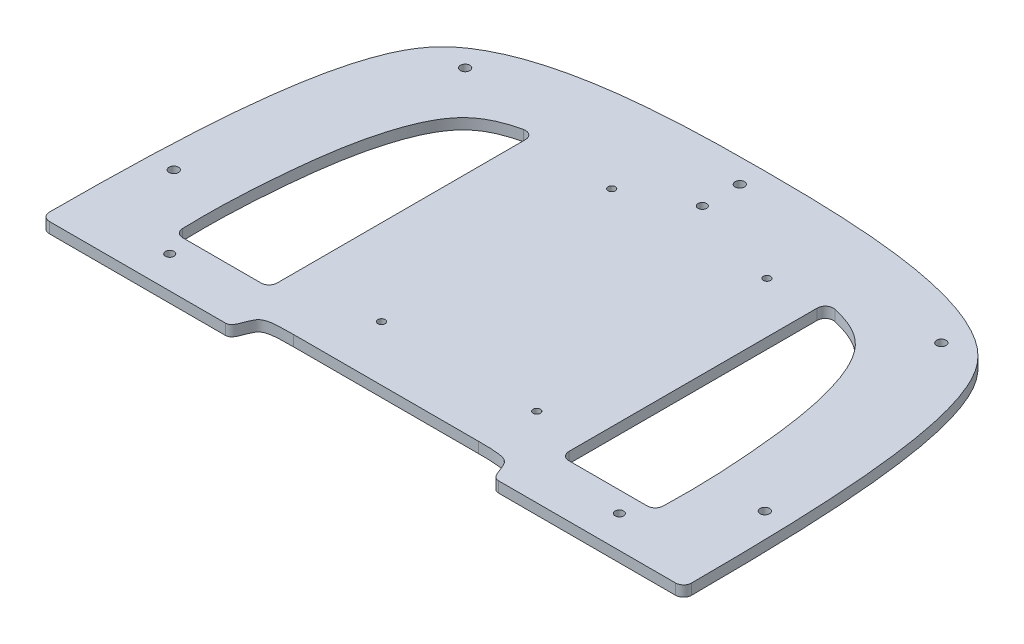
SolidWorks part; units mm, degrees
ref_plane "Front Plane" through (0, 0, 0) normal (0, 0, 1) x (1, 0, 0)
ref_plane "Top Plane" through (0, 0, 0) normal (0, 1, 0) x (1, 0, 0)
ref_plane "Right Plane" through (0, 0, 0) normal (1, 0, 0) x (0, 0, -1)
sketch "Sketch1" plane through (0, 0, 0) normal (0, 1, 0) x (1, 0, 0)
  line L1 (-120, 155) -> (120, 155)
  line L2 (-120, 155) -> (-120, -155)
  line L3 (-120, -155) -> (120, -155)
  line L4 (120, 155) -> (120, -155)
  point P4 (0, 155)
  point P6 (-120, 0)
  dimension "D1" = 240
  dimension "D2" = 310
extrude "Boss-Extrude1" add sketch "Sketch1" along normal blind 4 contours L2 L1 L4 L3
sketch "Sketch2" plane through (0, 4, 0) normal (0, 1, 0) x (1, 0, 0)
  line L0 (-120, 155) -> (120, 155) construction
  line L1 (-120, 0) -> (120, 0)
  line L2 (-120, 155) -> (-120, -155) construction
  circle B0 centre (49, -30) radius 1.75
  circle B1 centre (-49, -30) radius 1.75
  circle B2 centre (-88.957, -132.3382) radius 1.75
  circle B3 centre (0, -146) radius 1.75
  circle B4 centre (88.957, -132.3382) radius 1.75
  circle B5 centre (110.4185, 44.9345) radius 1.75
  circle B6 centre (88.957, 132.3382) radius 1.75
  circle B7 centre (0, 146) radius 1.75
  circle B8 centre (-88.957, 132.3382) radius 1.75
  circle B9 centre (-110.4185, 44.9345) radius 1.75
  spline B10 degree 3 poles (0, 155) (30.5722, 155) (80.3433, 153.7333) (119.2212, 117.6544) (120, 45.41) (120, 0) knots 0 0 0 0 0.458017 0.558017 1 1 1 1
  spline B11 degree 3 poles (0, 155) (-30.5722, 155) (-80.3433, 153.7333) (-119.2212, 117.6544) (-120, 45.41) (-120, 0) knots 0 0 0 0 0.458017 0.558017 1 1 1 1
  spline B12 degree 3 poles (0, -155) (30.5722, -155) (80.3433, -153.7333) (119.2212, -117.6544) (120, -45.41) (120, 0) knots 0 0 0 0 0.458017 0.558017 1 1 1 1
  spline B13 degree 3 poles (0, -155) (-30.5722, -155) (-80.3433, -153.7333) (-119.2212, -117.6544) (-120, -45.41) (-120, 0) knots 0 0 0 0 0.458017 0.558017 1 1 1 1
  line M2 (-120, -155) -> (120, -155)
  line M3 (120, -155) -> (120, 155)
  line M4 (120, 155) -> (-120, 155)
  line M5 (-120, 155) -> (-120, -155)
sketch_block_instance "Base-2-F1-1"
sketch_block "Base-2-F1"
extrude "Cut-Extrude1" cut sketch "Sketch2" against normal up to next contours B11 M4 M5 | B10 M4 M3 | B12 M2 M3 | B13 M2 M5 | B8 | B7 | B6 | B9 | B1 | B0 | B2 | B3 | B4 | B5
sketch "Sketch3" plane through (0, 4, 0) normal (0, 1, 0) x (1, 0, 0)
  line L1 (-120, 0) -> (120, 0)
  line L2 (-120, 0) -> (-120, -155)
  line L3 (-120, -155) -> (120, -155)
  line L4 (120, 0) -> (120, -155)
  line L5 (-120, 0) -> (120, 0)
  line L6 (-120, 0) -> (-120, 5)
  line L7 (-120, 5) -> (120, 5)
  line L8 (120, 0) -> (120, 5)
  point P9 (0, 5)
  circle M6 centre (88.957, -132.3382) radius 1.75
  circle M7 centre (0, -146) radius 1.75
  circle M11 centre (-49, -30) radius 1.75
  circle M12 centre (49, -30) radius 1.75
  circle M13 centre (-88.957, -132.3382) radius 1.75
  spline M15 degree 3 poles (0, 155) (-30.5722, 155) (-80.3433, 153.7333) (-119.2212, 117.6544) (-120, 45.41) (-120, 0) knots 0 0 0 0 0.458017 0.558017 1 1 1 1
  spline M16 degree 3 poles (-120, 0) (-120, -45.41) (-119.2212, -117.6544) (-80.3433, -153.7333) (-30.5722, -155) (0, -155) knots 0 0 0 0 0.441983 0.541983 1 1 1 1
  spline M17 degree 3 poles (0, -155) (30.5722, -155) (80.3433, -153.7333) (119.2212, -117.6544) (120, -45.41) (120, 0) knots 0 0 0 0 0.458017 0.558017 1 1 1 1
  spline M18 degree 3 poles (120, 0) (120, 45.41) (119.2212, 117.6544) (80.3433, 153.7333) (30.5722, 155) (0, 155) knots 0 0 0 0 0.441983 0.541983 1 1 1 1
  dimension "D1" = 155
  dimension "D2" = 5
extrude "Cut-Extrude2" cut sketch "Sketch3" against normal up to next contours L1 M16 M17 M6 M12 M13 M11 M7 | L7 L1 M15 M18
fillet "Fillet3" radius 3 2 edges
sketch "Sketch4" plane through (0, 4, 0) normal (0, 1, 0) x (1, 0, 0)
  line L0 (0, 5) -> (0, 144.25) construction
  line L1 (-54.5, 120.415) -> (-54.5, 27.625)
  line L2 (-57.5, 24.625) -> (-86.789, 24.625)
  line L3 (54.5, 120.415) -> (54.5, 27.625)
  line L4 (57.5, 24.625) -> (86.789, 24.625)
  line L5 (-116.9911, 5) -> (116.9911, 5) construction
  circle A0 centre (0, 146) radius 1.75 construction
  arc A1 (-54.5, 120.415) -> (-58.1637, 123.3407) centre (-57.5, 120.415) ccw
  arc A2 (-54.5, 27.625) -> (-57.5, 24.625) centre (-57.5, 27.625) cw
  arc A3 (-86.789, 24.625) -> (-89.7877, 27.5373) centre (-86.789, 27.625) cw
  arc A4 (54.5, 120.415) -> (58.1637, 123.3407) centre (57.5, 120.415) cw
  arc A5 (86.789, 24.625) -> (89.7877, 27.5373) centre (86.789, 27.625) ccw
  arc A6 (54.5, 27.625) -> (57.5, 24.625) centre (57.5, 27.625) ccw
  spline S0 degree 3 poles (-58.1637, 123.3407) (-67.2409, 121.2816) (-77.0217, 114.715) (-85.2116, 91.8938) (-89.0656, 63.3647) (-90.1983, 41.5749) (-89.7877, 27.5373) knots 0.021021 0.021021 0.021021 0.021021 0.204024 0.379971 0.619261 0.974387 0.974387 0.974387 0.974387
  spline S1 degree 3 poles (58.1637, 123.3407) (67.2409, 121.2816) (77.0217, 114.715) (85.2116, 91.8938) (89.0656, 63.3647) (90.1983, 41.5749) (89.7877, 27.5373) knots 0.021021 0.021021 0.021021 0.021021 0.204024 0.379971 0.619261 0.974387 0.974387 0.974387 0.974387
  point P0 (0, 24.625)
  point P5 (39.5, 74.625)
  point P6 (0, 74.625)
  point P21 (-54.5, 24.625)
  line B0 (-39.5, 124.625) -> (39.5, 124.625) construction
  line B1 (-39.5, 124.625) -> (-39.5, 24.625) construction
  line B2 (-39.5, 24.625) -> (39.5, 24.625) construction
  line B3 (39.5, 124.625) -> (39.5, 24.625) construction
  circle B4 centre (35.5, 120.625) radius 1.35
  circle B5 centre (-22.5, 120.625) radius 1.35
  circle B6 centre (-22.5, 34.625) radius 1.35
  circle B7 centre (35.5, 34.625) radius 1.35
  dimension "D3" = 3
  dimension "D1" = 15
sketch_block_instance "JETSON-NANO-1"
sketch_block "JETSON-NANO"
extrude "Cut-Extrude3" cut sketch "Sketch4" against normal up to next
sketch "Sketch6" plane through (0, 4, 0) normal (0, 1, 0) x (1, 0, 0)
  line L0 (-51.1698, 5) -> (50.8302, 5) construction
  line L1 (-34.7124, -4.0366) -> (34.3728, -4.0366) construction
  line L2 (-116.9911, 5) -> (116.9911, 5) construction
  line L3 (50.8302, 5) -> (-51.1698, 5)
  line L4 (-34.7124, 14.0366) -> (34.3728, 14.0366)
  spline S0 degree 3 poles (-51.1698, 5) (-49.2994, 5) (-47.7388, 0.3963) (-47.5462, 0.2227) (-45.7105, -3.741) (-41.8524, -4.0366) (-34.7124, -4.0366) knots 0 0 0 0 0.228374 0.4873 0.564462 1 1 1 1 construction
  spline S1 degree 3 poles (50.8302, 5) (48.9598, 5) (47.3992, 0.3963) (47.2066, 0.2227) (45.3709, -3.741) (41.5128, -4.0366) (34.3728, -4.0366) knots 0 0 0 0 0.228374 0.4873 0.564462 1 1 1 1 construction
  spline S2 degree 3 poles (50.8302, 5) (48.9598, 5) (47.3992, 9.6037) (47.2066, 9.7773) (45.3709, 13.741) (41.5128, 14.0366) (34.3728, 14.0366) knots 0 0 0 0 0.228374 0.4873 0.564462 1 1 1 1
  spline S3 degree 3 poles (-51.1698, 5) (-49.2994, 5) (-47.7388, 9.6037) (-47.5462, 9.7773) (-45.7105, 13.741) (-41.8524, 14.0366) (-34.7124, 14.0366) knots 0 0 0 0 0.228374 0.4873 0.564462 1 1 1 1
extrude "Cut-Extrude5" cut sketch "Sketch6" against normal blind 10
sketch "Sketch7" plane through (0, 4, 0) normal (0, 1, 0) x (1, 0, 0)
  line L0 (0, 155) -> (0, 0) construction
  line L3 (-84, 17) -> (84, 17) construction
  circle A0 centre (0, 132) radius 1.6
  circle A1 centre (-84, 17) radius 1.6
  circle A3 centre (84, 17) radius 1.6
  point P10 (0, 17)
  point P11 (0, 146)
  dimension "D1" = 3.2
  dimension "D2" = 168
  dimension "D3" = 17
  dimension "D4" = 14
extrude "Cut-Extrude6" cut sketch "Sketch7" against normal through all
